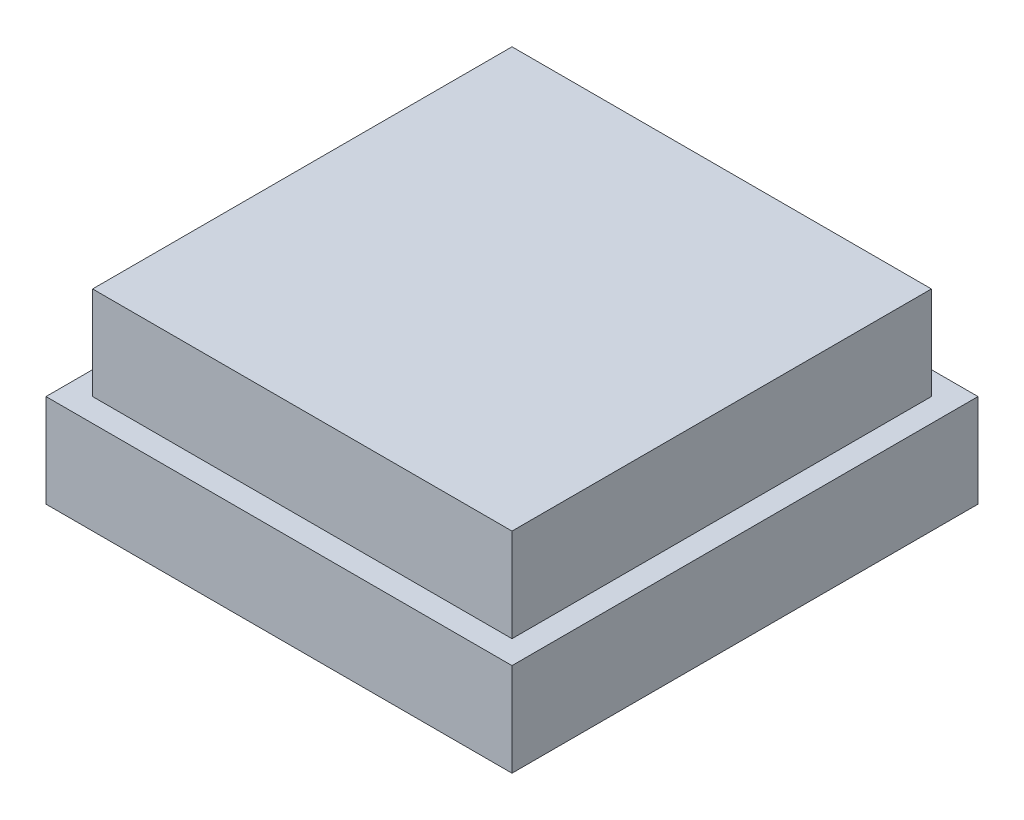
SolidWorks part; units mm, degrees
ref_plane "Front Plane" through (0, 0, 0) normal (0, 0, 1) x (1, 0, 0)
ref_plane "Top Plane" through (0, 0, 0) normal (0, 1, 0) x (1, 0, 0)
ref_plane "Right Plane" through (0, 0, 0) normal (1, 0, 0) x (0, 0, -1)
sketch "Sketch1" plane through (0, 0, 0) normal (0, 1, 0) x (1, 0, 0)
  line L1 (-25, 25) -> (25, 25)
  line L2 (-25, 25) -> (-25, -25)
  line L3 (-25, -25) -> (25, -25)
  line L4 (25, 25) -> (25, -25)
  line L5 (0, -25) -> (0, 25) construction
  line L6 (-25, 0) -> (25, 0) construction
  point P0 (0, 0)
  dimension "D1" = 50
  dimension "D2" = 50
extrude "Boss-Extrude1" add sketch "Sketch1" along normal blind 10
sketch "Sketch3" plane through (0, 10, 0) normal (0, 1, 0) x (1, 0, 0)
  line L1 (-22.5, 22.5) -> (22.5, 22.5)
  line L2 (-22.5, 22.5) -> (-22.5, -22.5)
  line L3 (-22.5, -22.5) -> (22.5, -22.5)
  line L4 (22.5, 22.5) -> (22.5, -22.5)
  line L5 (0, -22.5) -> (0, 22.5) construction
  line L6 (-22.5, 0) -> (22.5, 0) construction
  point P1 (0, 0)
  dimension "D1" = 45
  dimension "D2" = 45
extrude "Boss-Extrude2" add sketch "Sketch3" along normal blind 10 contours L1 L4 L3 L2
sketch "Sketch6" plane through (22.5, 0, 0) normal (1, 0, 0) x (0, 0, -1)
  line L0 (-22.5, 20) -> (22.5, 20) construction
